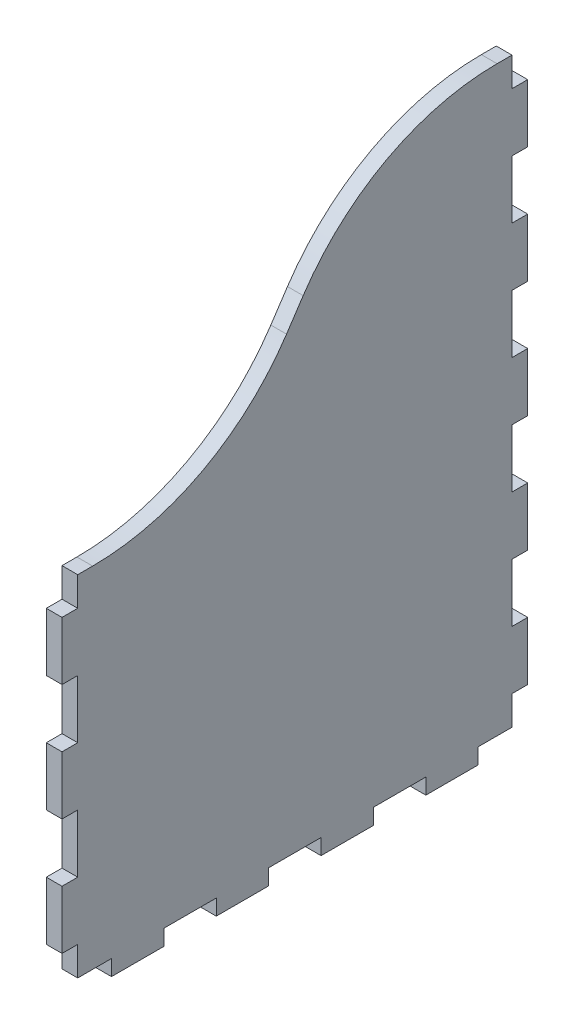
SolidWorks part; units mm, degrees
ref_plane "Plan de face" through (0, 0, 0) normal (0, 0, 1) x (1, 0, 0)
ref_plane "Plan de dessus" through (0, 0, 0) normal (0, 1, 0) x (1, 0, 0)
ref_plane "Plan de droite" through (0, 0, 0) normal (1, 0, 0) x (0, 0, -1)
sketch "Esquisse1" plane through (0, 0, 0) normal (1, 0, 0) x (0, 0, -1)
  line L0 (37.3, 100) -> (13.3, 100)
  line L2 (-37.3, 60) -> (-37.3, 0)
  line L3 (-37.3, 0) -> (37.3, 0)
  line L4 (37.3, 100) -> (37.3, 0)
  line L5 (13.3, 100) -> (-13.3, 60)
  line L6 (-13.3, 60) -> (-37.3, 60)
  line L7 (0, 80) -> (0, 0) construction
  dimension "D1" = 74.6
  dimension "D2" = 60
  dimension "D3" = 100
  dimension "D4" = 24
extrude "Boss.-Extru.1" add sketch "Esquisse1" along normal blind 2.7
sketch "Esquisse2" plane through (0, 0, 0) normal (1, 0, 0) x (0, 0, -1)
  line L0 (-37.3, 0) -> (37.3, 0) construction
  line L1 (-4.5, 0) -> (-13.5, 0)
  line L2 (-4.5, 0) -> (-4.5, -2.7)
  line L3 (-4.5, -2.7) -> (-13.5, -2.7)
  line L4 (-13.5, 0) -> (-13.5, -2.7)
  line L5 (-9, 0) -> (-9, -2.7) construction
  dimension "D1" = 9
  dimension "D2" = 9
  dimension "D3" = 2.7
extrude "Boss.-Extru.2" add sketch "Esquisse2" along normal blind 2.7
pattern_linear "Répétition linéaire1" count 3 spacing 18 along (0, 0, -1) count 2 spacing 18 along (0, 0, 1) of "Boss.-Extru.2"
sketch "Esquisse3" plane through (0, 0, 0) normal (1, 0, 0) x (0, 0, -1)
  line L0 (-37.3, 60) -> (-37.3, 0) construction
  line L1 (-37.3, 15) -> (-40, 15)
  line L2 (-37.3, 15) -> (-37.3, 5)
  line L3 (-37.3, 5) -> (-40, 5)
  line L4 (-40, 15) -> (-40, 5)
  line L5 (-40, 10) -> (-37.3, 10) construction
  line L6 (-37.3, 0) -> (-31.5, 0) construction
  dimension "D1" = 10
  dimension "D2" = 10
  dimension "D3" = 2.7
extrude "Boss.-Extru.3" add sketch "Esquisse3" along normal blind 2.7
pattern_linear "Répétition linéaire2" count 5 spacing 20 along (0, 1, 0) count 2 spacing 77.3 along (0, 0, -1) skipping (3, 0), (4, 0) of "Boss.-Extru.3"
fillet "Congé1" radius 40 2 edges at (1.35, 60, 13.3) (1.35, 100, -13.3)
